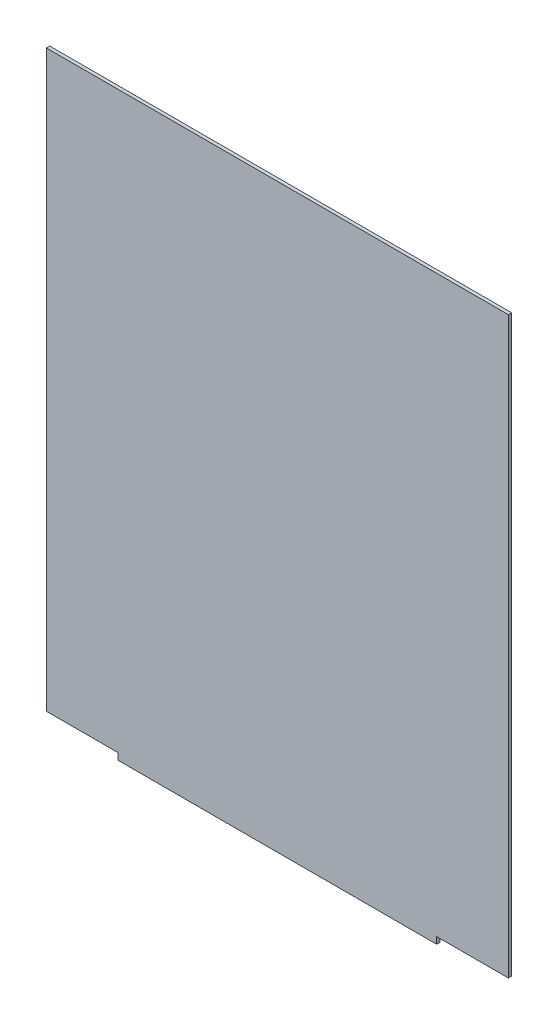
SolidWorks part; units mm, degrees
material "AISI 304"
ref_plane "Спереди" through (0, 0, 0) normal (0, 0, 1) x (1, 0, 0)
ref_plane "Сверху" through (0, 0, 0) normal (0, 1, 0) x (1, 0, 0)
ref_plane "Справа" through (0, 0, 0) normal (1, 0, 0) x (0, 0, -1)
sketch "Эскиз1" plane through (0, 0, 0) normal (0, 0, 1) x (1, 0, 0)
  line L1 (-209.5, -263.5) -> (209.5, -263.5)
  line L2 (-209.5, -263.5) -> (-209.5, 263.5)
  line L3 (-209.5, 263.5) -> (209.5, 263.5)
  line L4 (209.5, -263.5) -> (209.5, 263.5)
  line L5 (-209.5, -263.5) -> (209.5, 263.5) construction
  line L6 (-209.5, 263.5) -> (209.5, -263.5) construction
  point P0 (0, 0)
  dimension "D1" = 419
  dimension "D2" = 527
extrude "Бобышка-Вытянуть1" add sketch "Эскиз1" along normal blind 3
sketch "Эскиз2" plane through (0, 0, 0) normal (0, 0, -1) x (-1, 0, 0)
  line L0 (209.5, -263.5) -> (-209.5, -263.5) construction
  line L1 (209.5, 263.5) -> (209.5, -263.5) construction
  line L2 (0, 1.65) -> (0, -1.65) construction
  circle A0 centre (179.5, -232.5) radius 10
  circle A1 centre (-179.5, -232.5) radius 10
  dimension "D2" = 30
  dimension "D3" = 20
  dimension "D1" = 31
extrude "Вырез-Вытянуть1" [suppressed] cut sketch "Эскиз2" against normal blind 10
sketch "Эскиз3" plane through (0, 0, 3) normal (0, 0, -1) x (-1, 0, 0)
  line L0 (209.5, -263.5) -> (-209.5, -263.5) construction
  line L1 (-144.5, -263.5) -> (-209.5, -263.5)
  line L2 (-144.5, -263.5) -> (-144.5, -257.5)
  line L3 (-144.5, -257.5) -> (-209.5, -257.5)
  line L4 (-209.5, -263.5) -> (-209.5, -257.5)
  line L5 (-209.5, -263.5) -> (-209.5, 263.5) construction
  line L6 (144.5, -263.5) -> (209.5, -263.5)
  line L7 (144.5, -263.5) -> (144.5, -257.5)
  line L8 (144.5, -257.5) -> (209.5, -257.5)
  line L9 (209.5, -263.5) -> (209.5, -257.5)
  line L10 (209.5, -263.5) -> (-209.5, -263.5) construction
  line L11 (209.5, 263.5) -> (209.5, -263.5) construction
  dimension "D1" = 6
  dimension "D2" = 6
  dimension "D3" = 65
extrude "Вырез-Вытянуть5" cut sketch "Эскиз3" along normal up to surface (3 mm away) up to face at (0, 0, 0)
mirror "Зеркальное отражение1" [suppressed] about plane through (0, 0, 0) normal (0, 1, 0)
fillet "Скругление1" [suppressed] radius 20
